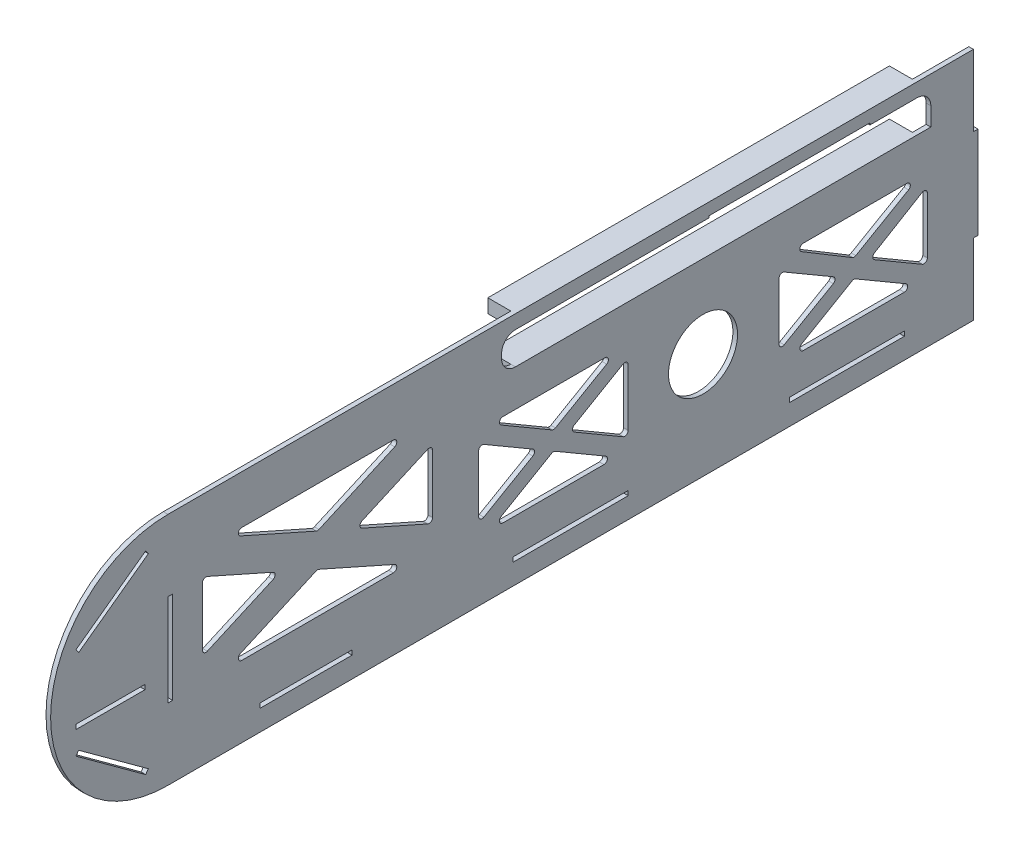
SolidWorks part; units mm, degrees
ref_plane "前视基准面" through (0, 0, 0) normal (0, 0, 1) x (1, 0, 0)
ref_plane "上视基准面" through (0, 0, 0) normal (0, 1, 0) x (1, 0, 0)
ref_plane "右视基准面" through (0, 0, 0) normal (1, 0, 0) x (0, 0, -1)
sketch "草图1" plane through (0, 0, 0) normal (1, 0, 0) x (0, 0, -1)
  line L0 (145, 39) -> (145, 37)
  line L1 (0, 51) -> (139, 51)
  line L2 (0, 51) -> (0, -51)
  line L3 (0, -51) -> (350, -51)
  line L4 (350, 51) -> (350, -51)
  line L5 (145, 51) -> (331.5, 51)
  line L6 (151, 31) -> (325.5, 31)
  line L7 (331.5, 39) -> (331.5, 36)
  line L8 (337.5, 51) -> (350, 51)
  line L9 (84.3341, 3.6293) -> (112.8908, -9.0626)
  line L10 (-40, -10) -> (-10, -10)
  line L11 (-40, -10) -> (-40, -8)
  line L12 (-40, -8) -> (-10, -8)
  line L13 (-10, -10) -> (-10, -8)
  line L14 (32.0683, 30) -> (97.9317, 30)
  line L15 (15, 17.6919) -> (15, -7.6919)
  line L16 (32.0683, -20) -> (97.9317, -20)
  line L17 (115, 17.6919) -> (115, -7.6919)
  line L18 (17.1092, 19.0626) -> (45.6659, 6.3707)
  line L19 (17.1092, -9.0626) -> (45.6659, 3.6293)
  line L20 (84.3341, 6.3707) -> (112.8908, 19.0626)
  line L21 (31.4591, 27.1293) -> (64.3908, 12.493)
  line L22 (145.5484, 15) -> (189.8851, 15)
  line L23 (135, 7.3884) -> (135, -17.3987)
  line L24 (145.5484, -25) -> (189.4516, -25)
  line L25 (200, 7.3884) -> (200, -17.3884)
  line L26 (65.6092, 12.493) -> (98.5409, 27.1293)
  line L27 (31.4591, -17.1293) -> (64.3908, -2.493)
  line L28 (65.6092, -2.493) -> (98.5409, -17.1293)
  line L29 (176.5069, -6.2957) -> (197.7442, -18.6841)
  line L30 (158.585, -3.7579) -> (137.2558, 8.6841)
  line L31 (137.2514, -18.6969) -> (158.5806, -6.3518)
  line L32 (176.5069, -3.7043) -> (197.7442, 8.6841)
  line L33 (144.7926, 12.2043) -> (166.8743, -0.6766)
  line L34 (190.6365, 12.2018) -> (168.3815, -0.6792)
  line L35 (168.2558, -9.3992) -> (190.2074, -22.2043)
  line L36 (144.7926, -22.2043) -> (166.7442, -9.3992)
  line L37 (276.0709, 15) -> (321.089, 15)
  line L38 (265.5225, 6.9941) -> (265.5225, -17.793)
  line L39 (276.0709, -25.3943) -> (319.9742, -25.3943)
  line L40 (330, 6.9941) -> (330, -17.478)
  line L41 (307.0294, -6.69) -> (327.7442, -18.7736)
  line L42 (289.1076, -4.1523) -> (267.7784, 8.2898)
  line L43 (267.7739, -19.0912) -> (289.1032, -6.7462)
  line L44 (307.0153, -4.107) -> (327.7301, 8.2815)
  line L45 (275.2981, 12.2144) -> (297.3797, -1.0609)
  line L46 (321.8404, 12.2018) -> (298.904, -1.0735)
  line L47 (298.7784, -9.7935) -> (320.73, -22.5987)
  line L48 (275.3151, -22.5987) -> (297.2667, -9.7935)
  line L49 (-40, 20) -> (-9.6982, 42.0918)
  line L50 (-40, 20) -> (-38.8218, 18.3839)
  line L51 (-9.6982, 42.0918) -> (-8.5199, 40.4757)
  line L52 (-38.8218, 18.3839) -> (-8.5199, 40.4757)
  line L53 (-51, 0) -> (0, 0)
  line L54 (-38.8218, -18.3839) -> (-8.5199, -40.4757)
  line L55 (-9.6982, -42.0918) -> (-8.5199, -40.4757)
  line L56 (-40, -20) -> (-38.8218, -18.3839)
  line L57 (-40, -20) -> (-9.6982, -42.0918)
  line L58 (40, -40) -> (80, -40)
  line L59 (40, -40) -> (40, -42)
  line L60 (80, -40) -> (80, -42)
  line L61 (40, -42) -> (80, -42)
  line L62 (150, -40) -> (200, -40)
  line L63 (150, -40) -> (150, -42)
  line L64 (200, -40) -> (200, -42)
  line L65 (150, -42) -> (200, -42)
  line L66 (270, -40) -> (320, -40)
  line L67 (270, -40) -> (270, -42)
  line L68 (320, -40) -> (320, -42)
  line L69 (270, -42) -> (320, -42)
  line L70 (350, 20) -> (352, 20)
  line L71 (350, 20) -> (350, -20)
  line L72 (352, 20) -> (352, -20)
  line L73 (350, -20) -> (352, -20)
  line L74 (0, 20) -> (0, -20)
  line L75 (0, 20) -> (2, 20)
  line L76 (0, -20) -> (2, -20)
  line L77 (2, 20) -> (2, -20)
  line L78 (139, 51) -> (145, 51)
  line L79 (331.5, 51) -> (337.5, 51)
  line L80 (151, 45) -> (325.5, 45)
  line L81 (151, 31) -> (151, 45)
  line L82 (145, 45) -> (145, 29)
  line L83 (151, 23) -> (325.5, 23)
  line L84 (331.5, 29) -> (331.5, 45)
  line L85 (325.5, 31) -> (331.5, 31)
  line L87 (235, 45) -> (305, 45)
  line L88 (235, 45) -> (235, 45.8)
  line L89 (235, 45.8) -> (305, 45.8)
  line L90 (305, 45) -> (305, 45.8)
  arc A0 (0, 51) -> (0, -51) centre (0, 0) ccw
  arc A1 (139, 51) -> (145, 45) centre (139, 45) cw
  arc A3 (151, 31) -> (145, 37) centre (151, 37) cw
  arc A4 (337.5, 51) -> (331.5, 45) centre (337.5, 45) ccw
  arc A5 (17.1092, 19.0626) -> (15, 17.6919) centre (16.5, 17.6919) ccw
  arc A6 (15, -7.6919) -> (17.1092, -9.0626) centre (16.5, -7.6919) ccw
  arc A7 (45.6659, 3.6293) -> (45.6659, 6.3707) centre (45.0567, 5) ccw
  arc A8 (84.3341, 6.3707) -> (84.3341, 3.6293) centre (84.9433, 5) ccw
  arc A9 (112.8908, -9.0626) -> (115, -7.6919) centre (113.5, -7.6919) ccw
  arc A10 (115, 17.6919) -> (112.8908, 19.0626) centre (113.5, 17.6919) ccw
  arc A11 (31.4591, -17.1293) -> (32.0683, -20) centre (32.0683, -18.5) ccw
  arc A12 (97.9317, -20) -> (98.5409, -17.1293) centre (97.9317, -18.5) ccw
  arc A13 (65.6092, -2.493) -> (64.3908, -2.493) centre (65, -3.8637) ccw
  arc A14 (97.9317, 30) -> (98.5409, 27.1293) centre (97.9317, 28.5) cw
  arc A15 (65.6092, 12.493) -> (64.3908, 12.493) centre (65, 13.8637) cw
  arc A16 (31.4591, 27.1293) -> (32.0683, 30) centre (32.0683, 28.5) cw
  arc A17 (197.7442, 8.6841) -> (200, 7.3884) centre (198.5, 7.3884) cw
  arc A18 (200, -17.3884) -> (197.7442, -18.6841) centre (198.5, -17.3884) cw
  arc A19 (176.5069, -6.2957) -> (176.5069, -3.7043) centre (177.2627, -5) cw
  arc A20 (158.585, -3.7579) -> (158.5806, -6.3518) centre (157.8292, -5.0536) cw
  arc A21 (137.2514, -18.6969) -> (135, -17.3987) centre (136.5, -17.3987) cw
  arc A22 (135, 7.3884) -> (137.2558, 8.6841) centre (136.5, 7.3884) cw
  arc A23 (144.7926, -22.2043) -> (145.5484, -25) centre (145.5484, -23.5) ccw
  arc A24 (189.4516, -25) -> (190.2074, -22.2043) centre (189.4516, -23.5) ccw
  arc A25 (168.2558, -9.3992) -> (166.7442, -9.3992) centre (167.5, -10.6949) ccw
  arc A26 (144.7926, 12.2043) -> (145.5484, 15) centre (145.5484, 13.5) cw
  arc A27 (189.8851, 15) -> (190.6365, 12.2018) centre (189.8851, 13.5) cw
  arc A28 (168.3815, -0.6792) -> (166.8743, -0.6766) centre (167.6301, 0.619) cw
  arc A29 (327.7301, 8.2815) -> (330, 6.9941) centre (328.5, 6.9941) cw
  arc A30 (330, -17.478) -> (327.7442, -18.7736) centre (328.5, -17.478) cw
  arc A31 (307.0294, -6.69) -> (307.0153, -4.107) centre (307.7852, -5.3943) cw
  arc A32 (289.1076, -4.1523) -> (289.1032, -6.7462) centre (288.3518, -5.4479) cw
  arc A33 (267.7739, -19.0912) -> (265.5225, -17.793) centre (267.0225, -17.793) cw
  arc A34 (265.5225, 6.9941) -> (267.7784, 8.2898) centre (267.0225, 6.9941) cw
  arc A35 (275.3151, -22.5987) -> (276.0709, -25.3943) centre (276.0709, -23.8943) ccw
  arc A36 (319.9742, -25.3943) -> (320.73, -22.5987) centre (319.9742, -23.8943) ccw
  arc A37 (298.7784, -9.7935) -> (297.2667, -9.7935) centre (298.0225, -11.0892) ccw
  arc A38 (275.2981, 12.2144) -> (276.0709, 15) centre (276.0709, 13.5) cw
  arc A39 (321.089, 15) -> (321.8404, 12.2018) centre (321.089, 13.5) cw
  arc A40 (298.904, -1.0735) -> (297.3797, -1.0609) centre (298.1526, 0.2247) cw
  circle A41 centre (232.5, -5) radius 15
  arc A42 (151, 23) -> (145, 29) centre (151, 29) cw
  arc A43 (331.5, 29) -> (325.5, 23) centre (325.5, 29) cw
  arc A44 (331.5, 39) -> (325.5, 45) centre (325.5, 39) ccw
  arc A45 (151, 45) -> (145, 39) centre (151, 39) ccw
  point P5 (145, 31)
  point P6 (145, 50)
  point P7 (331.5, 31)
  point P8 (331.5, 50)
  point P21 (145, 31)
  point P32 (105, 30)
  point P33 (25, 30)
  point P34 (25, -20)
  point P35 (105, -20)
  point P36 (65, 5)
  point P37 (115, 20)
  point P38 (15, -10)
  point P39 (15, 20)
  point P40 (115, -10)
  point P49 (48.75, 5)
  point P50 (65, -2.2222)
  point P51 (81.25, 5)
  point P52 (65, 12.2222)
  point P53 (140, 15)
  point P58 (195.4712, 15)
  point P59 (140, -25)
  point P60 (195, -25)
  point P61 (140, -25)
  point P62 (135, -20)
  point P63 (200, -20)
  point P64 (200, 10)
  point P65 (135, 10)
  point P86 (65, -2.2222)
  point P90 (65, 12.2222)
  point P124 (270.5225, 15)
  point P129 (325.9937, 15)
  point P130 (270.5225, -25.3943)
  point P131 (325.5225, -25.3943)
  point P132 (270.5225, -25.3943)
  point P133 (265.5225, -20.3943)
  point P134 (330, -20.3943)
  point P135 (330, 9.6057)
  point P136 (265.5225, 9.6057)
  point P169 (350, -20)
  point P182 (-9.6982, -42.0918)
  point P184 (-40, -20)
  point P189 (352, 20)
  point P190 (352, -20)
  point P198 (350, 20)
  point P209 (145, 23)
  point P224 (0, 0)
  dimension "D1" = 6
  dimension "D3" = 6
  dimension "D4" = 6
  dimension "D5" = 1.5
  dimension "D6" = 1.5
  dimension "D7" = 1.5
  dimension "D8" = 1.5
  dimension "D9" = 1.5
  dimension "D10" = 1.5
  dimension "D11" = 1.5
  dimension "D12" = 1.5
  dimension "D13" = 1.5
  dimension "D14" = 1.5
  dimension "D15" = 1.5
  dimension "D16" = 1.5
  dimension "D17" = 1.5
  dimension "D18" = 1.5
  dimension "D19" = 1.5
  dimension "D20" = 1.5
  dimension "D21" = 1.5
  dimension "D22" = 1.5
  dimension "D23" = 1.5
  dimension "D24" = 1.5
  dimension "D25" = 1.5
  dimension "D26" = 1.5
  dimension "D27" = 1.5
  dimension "D28" = 1.5
  dimension "D29" = 1.5
  dimension "D30" = 1.5
  dimension "D31" = 1.5
  dimension "D32" = 1.5
  dimension "D33" = 1.5
  dimension "D34" = 1.5
  dimension "D35" = 1.5
  dimension "D36" = 1.5
  dimension "D37" = 1.5
  dimension "D38" = 1.5
  dimension "D39" = 1.5
  dimension "D40" = 1.5
  dimension "D41" = 2
  dimension "D44" = 14
  dimension "D46" = 6
  dimension "D47" = 6
  dimension "D48" = 6
  dimension "D42" = 37.5
  dimension "D43" = 2
  dimension "D45" = 22
extrude "凸台-拉伸3" add sketch "草图1" along normal blind 2 contours L2 A0 L53 L52 L50 L49 L51 | L53 A0 L2 L57 L56 L54 L55 L13 L10 L11 L12 | L84 A43 L83 A42 L82 L0 A1 L1 L2 L75 L77 L76 L3 L4 L8 A4 L7 A41 A37 L47 A36 L39 A35 L48 A25 L35 A24 L24 A23 L36 A13 L28 A12 L16 A11 L27 A10 L17 A9 L9 | A45 L80 A44 L84 A4 L79 L5 L78 A1 L82 | A43 L84 L85 L6 A3 L82 A42 L83 | L4 L73 L72 L70
sketch "草图2" plane through (0, 0, 0) normal (1, 0, 0) x (0, 0, -1)
  line L0 (151, 45) -> (325.5, 45)
  line L1 (325.5, 45) -> (325.5, 51)
  line L2 (0, 51) -> (350, 51) construction
  line L3 (325.5, 51) -> (151, 51)
  line L4 (151, 51) -> (151, 45)
  line L5 (151, 31) -> (151, 24)
  line L6 (325.5, 23.5604) -> (325.5, 31)
  line L7 (151, 31) -> (331.5, 31) construction
  line L8 (325.5, 31) -> (151, 31)
  line L9 (151, 24) -> (325.5, 23.5604)
  line L10 (235, 45.8) -> (235, 45)
  line L11 (235, 45.8) -> (305, 45.8)
  line L12 (235, 45) -> (305, 45)
  line L13 (305, 45.8) -> (305, 45)
  line L14 (235, 45.8) -> (235, 51)
  line L15 (235, 45.8) -> (305, 45.8)
  line L16 (235, 51) -> (305, 51)
  line L17 (305, 45.8) -> (305, 51)
extrude "凸台-拉伸4" add sketch "草图2" against normal blind 10 contours L17 L13 L0 L1 L3 | L11 L17 L3 L14 | L10 L14 L3 L4 L0 | L5 L9 L6 L8
